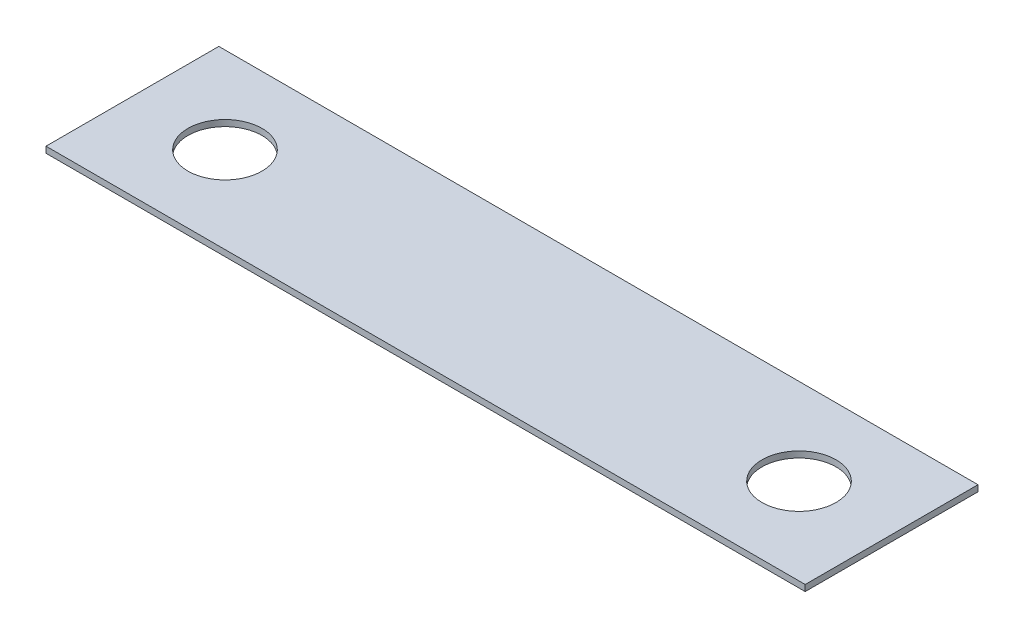
SolidWorks part; units mm, degrees
ref_plane "Ebene vorne" through (0, 0, 0) normal (0, 0, 1) x (1, 0, 0)
ref_plane "Ebene oben" through (0, 0, 0) normal (0, 1, 0) x (1, 0, 0)
ref_plane "Ebene rechts" through (0, 0, 0) normal (1, 0, 0) x (0, 0, -1)
sketch "Skizze1" plane through (0, 0, 0) normal (0, 1, 0) x (1, 0, 0)
  line L1 (61.5, -14) -> (-61.5, -14)
  line L2 (61.5, -14) -> (61.5, 14)
  line L3 (61.5, 14) -> (-61.5, 14)
  line L4 (-61.5, -14) -> (-61.5, 14)
  line L5 (61.5, -14) -> (-61.5, 14) construction
  line L6 (61.5, 14) -> (-61.5, -14) construction
  point P0 (0, 0)
  dimension "D1" = 28
  dimension "D2" = 123
extrude "Aufsatz-Linear austragen1" add sketch "Skizze1" along normal blind 1
sketch "Skizze2" plane through (0, 1, 0) normal (0, 1, 0) x (1, 0, 0)
  line L0 (-61.5, 14) -> (-61.5, -14) construction
  line L1 (-61.5, -14) -> (61.5, -14) construction
  line L2 (61.5, -14) -> (61.5, 14) construction
  circle A0 centre (46.5, 0) radius 6
  circle A1 centre (-46.5, 0) radius 6
  dimension "D1" = 12
  dimension "D2" = 12
  dimension "D3" = 15
  dimension "D4" = 14
  dimension "D5" = 14
  dimension "D6" = 15
extrude "Schnitt-Linear austragen1" cut sketch "Skizze2" against normal through all
